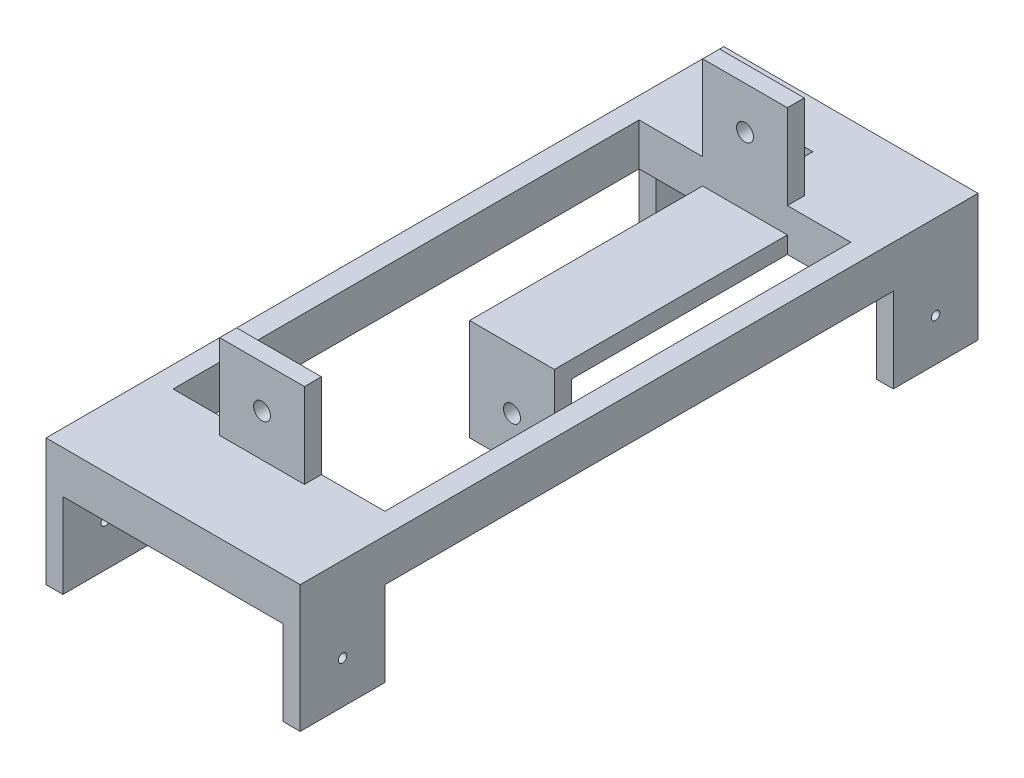
SolidWorks part; units mm, degrees
other "Markup1"
sketch "Sketch19" plane through (-15, 15, -40) normal (-0.0389, 0.0826, -0.9958) x (-0.519, -0.8533, -0.0505)
ref_plane "Front Plane" through (0, 0, 0) normal (0, 0, 1) x (1, 0, 0)
ref_plane "Top Plane" through (0, 0, 0) normal (0, 1, 0) x (1, 0, 0)
ref_plane "Right Plane" through (0, 0, 0) normal (1, 0, 0) x (0, 0, -1)
sketch "Sketch1" plane through (0, 0, 0) normal (0, 1, 0) x (1, 0, 0)
  line L1 (-15, 40) -> (15, 40)
  line L2 (-15, 40) -> (-15, -40)
  line L3 (-15, -40) -> (15, -40)
  line L4 (15, 40) -> (15, -40)
  line L5 (-15, 40) -> (15, -40) construction
  line L6 (-15, -40) -> (15, 40) construction
  point P0 (0, 0)
  dimension "D1" = 30
  dimension "D2" = 80
extrude "Boss-Extrude1" add sketch "Sketch1" along normal blind 5
sketch "Sketch2" plane through (15, 0, 0) normal (1, 0, 0) x (0, 0, -1)
  line L1 (-40, 0) -> (-30, 0)
  line L2 (-40, 0) -> (-40, -10)
  line L3 (-40, -10) -> (-30, -10)
  line L4 (-30, 0) -> (-30, -10)
  line L5 (40, 0) -> (30, 0)
  line L6 (40, 0) -> (40, -10)
  line L7 (40, -10) -> (30, -10)
  line L8 (30, 0) -> (30, -10)
  dimension "D1" = 10
  dimension "D2" = 10
  dimension "D3" = 10
  dimension "D4" = 10
extrude "Boss-Extrude2" add sketch "Sketch2" against normal blind 30
sketch "Sketch3" plane through (15, 0, 0) normal (1, 0, 0) x (0, 0, -1)
  line L0 (-40, 5) -> (-40, -10) construction
  line L2 (-40, -10) -> (-30, -10) construction
  line L3 (30, -10) -> (40, -10) construction
  line L4 (30, 0) -> (30, -10) construction
  circle A0 centre (-35, -5) radius 0.5
  circle A1 centre (35, -5) radius 0.5
  dimension "D1" = 1
  dimension "D2" = 1
  dimension "D3" = 5
  dimension "D4" = 5
  dimension "D5" = 5
  dimension "D6" = 5
extrude "Cut-Extrude1" cut sketch "Sketch3" against normal through all both and the other way through all
sketch "Sketch4" plane through (0, 5, 0) normal (0, 1, 0) x (1, 0, 0)
  line L9 (-12.5, -27.5) -> (12.5, -27.5)
  line L10 (-12.5, -27.5) -> (-12.5, 27.5)
  line L11 (-12.5, 27.5) -> (12.5, 27.5)
  line L12 (12.5, -27.5) -> (12.5, 27.5)
  line L13 (-12.5, -27.5) -> (12.5, 27.5) construction
  line L14 (-12.5, 27.5) -> (12.5, -27.5) construction
  point P0 (0, 0)
  dimension "D1" = 55
  dimension "D2" = 25
extrude "Cut-Extrude2" cut sketch "Sketch4" against normal through all both and the other way through all
sketch "Sketch5" plane through (0, 0, -40) normal (0, 0, -1) x (-1, 0, 0)
  line L0 (15, -10) -> (-15, -10) construction
  line L1 (-13, -10) -> (13, -10)
  line L2 (-13, -10) -> (-13, 0)
  line L3 (-13, 0) -> (13, 0)
  line L4 (13, -10) -> (13, 0)
  line L5 (-15, 5) -> (-15, -10) construction
  line L6 (15, 5) -> (15, -10) construction
  dimension "D1" = 10
  dimension "D2" = 2
  dimension "D3" = 2
extrude "Cut-Extrude3" cut sketch "Sketch5" against normal through all both and the other way through all
sketch "Sketch6" plane through (0, 0, -40) normal (0, 0, -1) x (-1, 0, 0)
  line L0 (-13, 0) -> (13, 0) construction
  line L1 (-5, 0) -> (5, 0)
  line L2 (-5, 0) -> (-5, -10)
  line L3 (-5, -10) -> (5, -10)
  line L4 (5, 0) -> (5, -10)
  line L6 (-13, -10) -> (-13, 0) construction
  line L7 (13, 0) -> (13, -10) construction
  dimension "D1" = 8
  dimension "D2" = 10
  dimension "D3" = 8
extrude "Boss-Extrude3" add sketch "Sketch6" against normal blind 80
sketch "Sketch7" plane through (0, 0, -40) normal (0, 0, -1) x (-1, 0, 0)
  line L0 (-5, 0) -> (-5, -10) construction
  line L1 (-5, -10) -> (5, -10) construction
  circle A0 centre (0, -5) radius 1
  point P4 (-5, -5)
  dimension "D1" = 2
  dimension "D2" = 5
  dimension "D3" = 5
extrude "Cut-Extrude4" cut sketch "Sketch7" against normal through all both and the other way through all
sketch "Sketch8" plane through (5, 0, 0) normal (1, 0, 0) x (0, 0, -1)
  line L0 (-40, -10) -> (40, -10) construction
  line L1 (-28, -10) -> (28, -10)
  line L2 (-28, -10) -> (-28, 0)
  line L3 (-28, 0) -> (28, 0)
  line L4 (28, -10) -> (28, 0)
  line L5 (-27.5, 0) -> (27.5, 0) construction
  line L6 (-30, -10) -> (-30, 0) construction
  line L7 (30, 0) -> (30, -10) construction
  dimension "D1" = 2
  dimension "D2" = 2
extrude "Cut-Extrude5" cut sketch "Sketch8" against normal through all both and the other way through all
sketch "Sketch9" plane through (0, 0, 40) normal (0, 0, 1) x (1, 0, 0)
  line L1 (-5, -10) -> (5, -10)
  line L2 (-5, -10) -> (-5, 0)
  line L3 (-5, 0) -> (5, 0)
  line L4 (5, -10) -> (5, 0)
extrude "Cut-Extrude6" cut sketch "Sketch9" against normal blind 10
sketch "Sketch10" plane through (0, 0, -40) normal (0, 0, -1) x (-1, 0, 0)
  line L1 (-5, -10) -> (5, -10)
  line L2 (-5, -10) -> (-5, 0)
  line L3 (-5, 0) -> (5, 0)
  line L4 (5, -10) -> (5, 0)
extrude "Cut-Extrude7" cut sketch "Sketch10" against normal blind 10
sketch "Sketch12" plane through (0, 5, 0) normal (0, 1, 0) x (1, 0, 0)
  line L0 (-12.5, -27.5) -> (12.5, -27.5) construction
  line L1 (-5, -27.5) -> (5, -27.5)
  line L2 (-5, -27.5) -> (-5, -29.5)
  line L3 (-5, -29.5) -> (5, -29.5)
  line L4 (5, -27.5) -> (5, -29.5)
  line L5 (12.5, 27.5) -> (-12.5, 27.5) construction
  line L6 (5, 27.5) -> (-5, 27.5)
  line L7 (5, 27.5) -> (5, 29.5)
  line L8 (5, 29.5) -> (-5, 29.5)
  line L9 (-5, 27.5) -> (-5, 29.5)
  line L10 (15, -40) -> (15, 40) construction
  dimension "D1" = 2
  dimension "D2" = 10
  dimension "D3" = 10
  dimension "D4" = 2
  dimension "D5" = 10
  dimension "D6" = 10
extrude "Boss-Extrude5" add sketch "Sketch12" along normal blind 10
sketch "Sketch13" plane through (0, 0, 29.5) normal (0, 0, 1) x (1, 0, 0)
  line L0 (-5, 15) -> (-5, 5) construction
  line L1 (-5, 5) -> (5, 5) construction
  circle A0 centre (0, 10) radius 1
  dimension "D1" = 2
  dimension "D2" = 5
  dimension "D3" = 5
extrude "Cut-Extrude8" cut sketch "Sketch13" against normal through all both and the other way through all contours A0
sketch "Sketch15" plane through (0, 5, 0) normal (0, 1, 0) x (1, 0, 0)
  line L0 (5, 29.5) -> (-5, 29.5) construction
  line L1 (-1, 32.5) -> (1, 32.5)
  line L2 (-1, 32.5) -> (-1, 34.5)
  line L3 (-1, 34.5) -> (1, 34.5)
  line L4 (1, 32.5) -> (1, 34.5)
  line L5 (-1, 32.5) -> (1, 34.5) construction
  line L6 (-1, 34.5) -> (1, 32.5) construction
  line L7 (5, 27.5) -> (5, 29.5) construction
  point P0 (0, 33.5)
  dimension "D1" = 2
  dimension "D2" = 2
  dimension "D3" = 4
  dimension "D4" = 4
extrude "Cut-Extrude11" cut sketch "Sketch15" against normal through all both and the other way through all
sketch "Sketch16" plane through (0, 0, -30) normal (0, 0, -1) x (-1, 0, 0)
  line L4 (-5, 0) -> (-5, -10)
  line L5 (-5, -10) -> (5, -10)
  line L6 (5, -10) -> (5, 0)
  line L7 (5, 0) -> (-5, 0)
  line L8 (-5, 0) -> (-5, -10)
  line L9 (-5, -10) -> (5, -10)
  line L10 (5, -10) -> (5, 0)
  line L11 (5, 0) -> (-5, 0)
  dimension "D1" = 0
extrude "Boss-Extrude6" add sketch "Sketch16" against normal blind 30
sketch "Sketch17" plane through (0, 0, -30) normal (0, 0, -1) x (-1, 0, 0)
  line L1 (-5, -10) -> (5, -10)
  line L2 (-5, -10) -> (-5, 0)
  line L3 (-5, 0) -> (5, 0)
  line L4 (5, -10) -> (5, 0)
extrude "Cut-Extrude12" cut sketch "Sketch17" against normal blind 28
sketch "Sketch18" plane through (0, 0, -2) normal (0, 0, -1) x (-1, 0, 0)
  line L0 (-5, -10) -> (5, -10) construction
  line L2 (-5, 0) -> (-5, -10) construction
  circle A0 centre (0, -5) radius 1
  point P4 (0, 0)
  point P5 (0, -5)
  point P6 (-10, -5)
  dimension "D3" = 2
  dimension "D1" = 5
  dimension "D2" = 5
extrude "Cut-Extrude13" cut sketch "Sketch18" against normal through all both and the other way through all
sketch "Sketch20" plane through (0, 0, -40) normal (0, 0, -1) x (-1, 0, 0)
  line L1 (-5, 0) -> (5, 0)
  line L2 (-5, 0) -> (-5, 2)
  line L3 (-5, 2) -> (5, 2)
  line L4 (5, 0) -> (5, 2)
  dimension "D1" = 10
  dimension "D2" = 2
extrude "Boss-Extrude7" add sketch "Sketch20" against normal blind 40
equation "\"w\"=3.9113"
